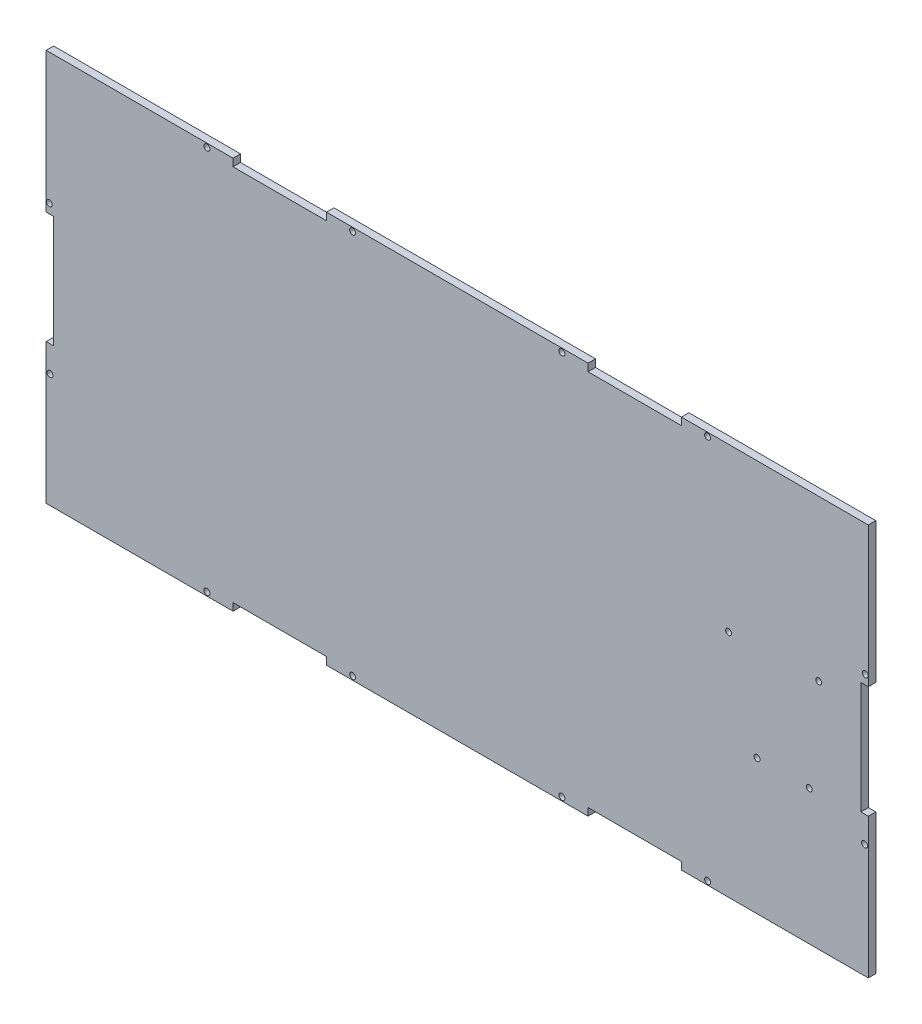
SolidWorks part; units mm, degrees
ref_plane "Plan de face" through (0, 0, 0) normal (0, 0, 1) x (1, 0, 0)
ref_plane "Plan de dessus" through (0, 0, 0) normal (0, 1, 0) x (1, 0, 0)
ref_plane "Plan de droite" through (0, 0, 0) normal (1, 0, 0) x (0, 0, -1)
sketch "Esquisse1" plane through (0, 0, 0) normal (0, 0, 1) x (1, 0, 0)
  line L1 (220, -105) -> (-220, -105)
  line L2 (220, -105) -> (220, 105)
  line L3 (220, 105) -> (-220, 105)
  line L4 (-220, -105) -> (-220, 105)
  line L5 (220, -105) -> (-220, 105) construction
  line L6 (220, 105) -> (-220, -105) construction
  point P0 (0, 0)
  dimension "D1" = 440
  dimension "D2" = 210
extrude "Boss.-Extru.1" add sketch "Esquisse1" along normal blind 4
sketch "Esquisse2" plane through (0, 0, 4) normal (0, 0, 1) x (1, 0, 0)
  line L0 (220, 105) -> (-220, 105) construction
  line L1 (-120, 101) -> (-70, 101)
  line L2 (-120, 101) -> (-120, 105)
  line L3 (-120, 105) -> (-70, 105)
  line L4 (-70, 101) -> (-70, 105)
  line L5 (-70, 101) -> (-70, 105) construction
  line L6 (70, 101) -> (70, 105) construction
  line L7 (120, 101) -> (70, 101)
  line L8 (120, 101) -> (120, 105)
  line L9 (120, 105) -> (70, 105)
  line L10 (70, 101) -> (70, 105)
  line L11 (220, -105) -> (220, 105) construction
  line L12 (216, -30) -> (220, -30)
  line L13 (216, -30) -> (216, 30)
  line L14 (216, 30) -> (220, 30)
  line L15 (220, -30) -> (220, 30)
  line L16 (216, 30) -> (220, 30) construction
  line L17 (-220, 105) -> (-220, -105) construction
  line L18 (-220, 30) -> (-216, 30)
  line L19 (-220, 30) -> (-220, -30)
  line L20 (-220, -30) -> (-216, -30)
  line L21 (-216, 30) -> (-216, -30)
  line L22 (-220, 30) -> (-216, 30) construction
  line L23 (83.2841, 0) -> (-109.6801, 0) construction
  line L24 (70, -101) -> (70, -105)
  line L25 (120, -101) -> (70, -101)
  line L26 (120, -105) -> (70, -105)
  line L27 (120, -101) -> (120, -105)
  line L28 (-70, -101) -> (-70, -105)
  line L29 (-120, -105) -> (-70, -105)
  line L30 (-120, -101) -> (-70, -101)
  line L31 (-120, -101) -> (-120, -105)
  point P37 (-70, 103)
  point P42 (-70, -103)
extrude "Enlèv. mat.-Extru.1" cut sketch "Esquisse2" against normal blind 4
sketch "Esquisse4" plane through (0, 0, 4) normal (0, 0, 1) x (1, 0, 0)
  line L0 (-220, -105) -> (-120, -105) construction
  line L1 (-120, -101) -> (-120, -105) construction
  line L2 (-70, -105) -> (-70, -101) construction
  line L3 (-70, -105) -> (70, -105) construction
  line L4 (-220, -30) -> (-220, -105) construction
  line L5 (-220, -30) -> (-216, -30) construction
  line L7 (25.3459, 0) -> (-113.1521, 0) construction
  line L8 (0, -57.3869) -> (0, 67.9872) construction
  line L9 (-216, 30) -> (-220, 30) construction
  line L10 (220, 105) -> (120, 105) construction
  circle A0 centre (-134, -103) radius 1.6
  circle A1 centre (-56, -103) radius 1.6
  circle A2 centre (-218, -44) radius 1.6
  circle A3 centre (-218.3751, 35) radius 1.6
  circle A4 centre (-218.3751, 35) radius 1.6 construction
  circle A5 centre (-218.3751, 35) radius 1.6
  circle A6 centre (-56, 103) radius 1.6
  circle A7 centre (-134, 103) radius 1.6
  circle A8 centre (56, -103) radius 1.6
  circle A9 centre (134, -103) radius 1.6
  circle A10 centre (218.3751, 35) radius 1.6
  circle A11 centre (218.3751, 35) radius 1.6
  circle A12 centre (218, -44) radius 1.6
  circle A13 centre (134, 103) radius 1.6
  circle A14 centre (56, 103) radius 1.6
  dimension "D1" = 3.2
  dimension "D4" = 14
  dimension "D5" = 2
  dimension "D6" = 3.2
  dimension "D7" = 3.2
  dimension "D8" = 2
  dimension "D9" = 14
  dimension "D10" = 5
  dimension "D11" = 3.2
  dimension "D12" = 3.2
  dimension "D2" = 2
  dimension "D3" = 14
  dimension "D13" = 2
extrude "Enlèv. mat.-Extru.2" cut sketch "Esquisse4" against normal blind 10 contours A12 | A10 | A6 | A7 | A3 | A1 | A0 | A13 | A14 | A2 | A8 | A9
sketch "Esquisse5" plane through (0, 0, 0) normal (0, 0, -1) x (-1, 0, 0)
  circle A0 centre (-145.2167, 18.0104) radius 1.5875
  circle A1 centre (-160.4356, -32.78) radius 1.5984
  circle A2 centre (-188.38, -32.79) radius 1.5875
  circle A3 centre (-193.46, 19.28) radius 1.5875
extrude "Enlèv. mat.-Extru.3" cut sketch "Esquisse5" against normal blind 4
